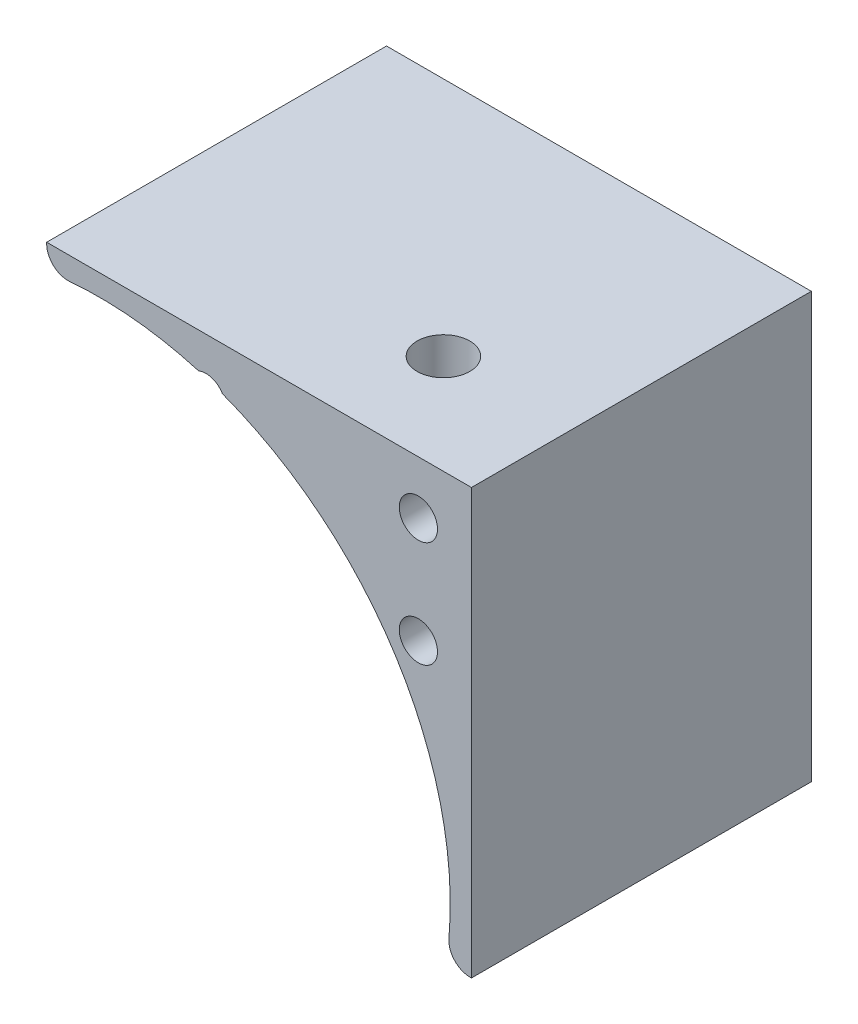
SolidWorks part; units mm, degrees
ref_plane "Front Plane" through (0, 0, 0) normal (0, 0, 1) x (1, 0, 0)
ref_plane "Top Plane" through (0, 0, 0) normal (0, 1, 0) x (1, 0, 0)
ref_plane "Right Plane" through (0, 0, 0) normal (1, 0, 0) x (0, 0, -1)
sketch "Sketch1" plane through (0, 0, 0) normal (0, 0, 1) x (1, 0, 0)
  line L1 (0, 0) -> (50.8, 0)
  line L2 (0, 0) -> (0, 50.8)
  line L3 (0, 50.8) -> (50.8, 50.8)
  line L4 (50.8, 0) -> (50.8, 50.8)
  dimension "D1" = 50.8
  dimension "D2" = 50.8
extrude "Boss-Extrude1" add sketch "Sketch1" along normal blind 40.64
sketch "Sketch2" plane through (0, 0, 40.64) normal (0, 0, 1) x (1, 0, 0)
  circle A0 centre (6.35, 6.35) radius 41.91
  dimension "D1" = 83.82
extrude "Cut-Extrude1" cut sketch "Sketch2" against normal blind 26.67
sketch "Sketch3" plane through (0, 0, 0) normal (0, 0, -1) x (-1, 0, 0)
  circle A0 centre (-6.35, 6.35) radius 29.21
  dimension "D1" = 58.42
extrude "Cut-Extrude2" cut sketch "Sketch3" against normal through all
sketch "Sketch4" plane through (0, 0, 0) normal (0, 0, -1) x (-1, 0, 0)
  circle A0 centre (-6.35, 44.45) radius 2.286
  circle A1 centre (-19.05, 44.45) radius 2.286
  circle A2 centre (-44.45, 44.45) radius 2.286
  circle A3 centre (-44.45, 31.75) radius 2.286
  point P10 (0, 0)
  point P11 (0, 0)
  point P12 (-44.45, 44.45)
  point P14 (-44.45, 31.75)
  dimension "D1" = 4.572
extrude "Cut-Extrude3" cut sketch "Sketch4" against normal through all
fillet "Fillet1" radius 2.54 4 edges at (47.7761, 0, 27.305) (34.8614, 0, 6.985) (0, 47.7761, 27.305) (0, 34.8614, 6.985)
sketch "Sketch5" plane through (0, 50.8, 0) normal (0, 1, 0) x (1, 0, 0)
  circle A0 centre (35.5321, -28.7241) radius 3.1543
extrude "Cut-Extrude4" cut sketch "Sketch5" against normal through all
